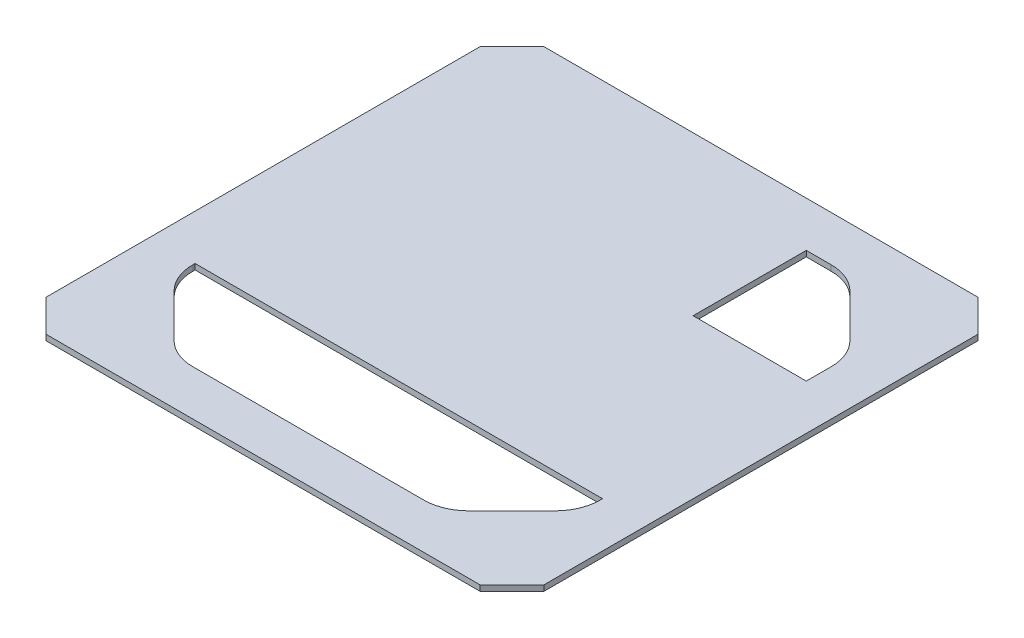
SolidWorks part; units mm, degrees
material "Thornel Mat VMA"
ref_plane "Front Plane" through (0, 0, 0) normal (0, 0, 1) x (1, 0, 0)
ref_plane "Top Plane" through (0, 0, 0) normal (0, 1, 0) x (1, 0, 0)
ref_plane "Right Plane" through (0, 0, 0) normal (1, 0, 0) x (0, 0, -1)
sketch "Sketch1" plane through (0, 0, 0) normal (0, 1, 0) x (1, 0, 0)
  line L0 (-139.7, 73.5201) -> (-121.7395, 91.4807)
  line L1 (-121.7395, 91.4807) -> (121.7395, 91.4807)
  line L2 (-139.7, 73.5201) -> (-139.7, -169.9588)
  line L3 (139.7, 73.5201) -> (139.7, -169.9588)
  line L4 (139.7, 73.5201) -> (121.7395, 91.4807)
  line L5 (0, 91.4807) -> (0, -187.9193) construction
  line L6 (-139.7, -48.2193) -> (139.7, -48.2193) construction
  line L7 (139.7, -169.9588) -> (121.7395, -187.9193)
  line L8 (-121.7395, -187.9193) -> (121.7395, -187.9193)
  line L9 (-139.7, -169.9588) -> (-121.7395, -187.9193)
  line L10 (-247.4631, 199.2437) -> (247.4631, 199.2437) construction
  line L11 (247.4631, 199.2437) -> (247.4631, -295.6824) construction
  line L12 (247.4631, -295.6824) -> (-247.4631, -295.6824) construction
  line L13 (-247.4631, -295.6824) -> (-247.4631, 199.2437) construction
  line L14 (-247.4631, 199.2437) -> (247.4631, -295.6824) construction
  line L15 (-247.4631, -295.6824) -> (247.4631, 199.2437) construction
  line L16 (-247.4631, 199.2437) -> (-130.7197, 82.5004) construction
  point P11 (0, -48.2193)
  point P20 (0, -48.2193)
  point P21 (-130.7197, 82.5004)
  dimension "D1" = 279.4
  dimension "D2" = 279.4
  dimension "D3" = 25.4
  dimension "D4" = 165.1
extrude "Boss-Extrude1" add sketch "Sketch1" along normal blind 3.175
sketch "Sketch2" plane through (0, 3.175, 0) normal (0, 1, 0) x (1, 0, 0)
  line L0 (-139.7, -48.2193) -> (139.7, -48.2193) construction
  line L1 (-139.7, 73.5201) -> (-139.7, -169.9588) construction
  line L2 (-103.779, 37.5991) -> (-114.3, 27.0781)
  line L3 (0, 91.4807) -> (0, -187.9193) construction
  line L4 (-85.8185, 55.5596) -> (-75.2974, 66.0807)
  line L5 (-130.7197, 82.5004) -> (-94.7987, 46.5794) construction
  line L6 (121.7395, 91.4807) -> (-121.7395, 91.4807) construction
  line L7 (-121.7395, -187.9193) -> (121.7395, -187.9193) construction
  line L8 (139.7, -169.9588) -> (139.7, 73.5201) construction
  line L9 (-114.3, 27.0781) -> (-114.3, -123.5168)
  line L10 (-121.7395, 91.4807) -> (-139.7, 73.5201) construction
  line L11 (-75.2974, 66.0807) -> (75.2974, 66.0807)
  line L12 (114.3, 27.0781) -> (114.3, -123.5168)
  line L13 (85.8185, 55.5596) -> (103.779, 37.5991)
  line L14 (85.8185, 55.5596) -> (75.2974, 66.0807)
  line L15 (103.779, 37.5991) -> (114.3, 27.0781)
  line L16 (-85.8185, -151.9983) -> (-103.779, -134.0378)
  line L17 (103.779, -134.0378) -> (114.3, -123.5168)
  line L18 (85.8185, -151.9983) -> (75.2974, -162.5193)
  line L19 (85.8185, -151.9983) -> (103.779, -134.0378)
  line L20 (-75.2974, -162.5193) -> (75.2974, -162.5193)
  line L21 (-85.8185, -151.9983) -> (-75.2974, -162.5193)
  line L22 (-103.779, -134.0378) -> (-114.3, -123.5168)
  line L23 (-85.8185, 55.5596) -> (-103.779, 37.5991)
  point P22 (114.3, -48.2193)
  point P26 (-114.3, -48.2193)
  dimension "D3" = 25.4
  dimension "D4" = 25.4
  dimension "D1" = 50.8
  dimension "D2" = 25.4
extrude "Cut-Extrude4" cut sketch "Sketch2" against normal through all
sketch "Sketch5" plane through (0, 3.175, 0) normal (0, 1, 0) x (1, 0, 0)
  line L0 (0, 91.4807) -> (0, -187.9193) construction
  line L1 (121.7395, 91.4807) -> (-121.7395, 91.4807) construction
  line L2 (139.7, -48.2193) -> (-139.7, -48.2193) construction
  line L3 (139.7, -169.9588) -> (139.7, 73.5201) construction
  line L4 (-121.7395, -187.9193) -> (121.7395, -187.9193) construction
  line L5 (-139.7, 73.5201) -> (-139.7, -169.9588) construction
  line L6 (-247.4631, 199.2437) -> (247.4631, 199.2437) construction
  line L7 (247.4631, 199.2437) -> (247.4631, -295.6824) construction
  line L8 (247.4631, -295.6824) -> (-247.4631, -295.6824) construction
  line L9 (-247.4631, -295.6824) -> (-247.4631, 199.2437) construction
  line L10 (139.7, -48.2193) -> (358.8347, -48.2193) construction
  line L11 (0, 91.4807) -> (0, 307.0068) construction
  line L12 (-247.4631, 199.2437) -> (247.4631, -295.6824) construction
  line L13 (247.4631, 199.2437) -> (-247.4631, -295.6824) construction
  line L14 (-121.7395, 91.4807) -> (-139.7, 73.5201) construction
  line L15 (-247.4631, 199.2437) -> (-94.7987, 46.5794) construction
  line L16 (-75.2974, 66.0807) -> (-114.3, 27.0781) construction
  circle A0 centre (-121.7395, 73.5201) radius 2.54
  circle A1 centre (-103.779, 55.5596) radius 2.54
  circle A2 centre (103.779, 55.5596) radius 2.54
  circle A3 centre (121.7395, 73.5201) radius 2.54
  circle A4 centre (121.7395, -169.9588) radius 2.54
  circle A5 centre (103.779, -151.9983) radius 2.54
  circle A6 centre (-103.779, -151.9983) radius 2.54
  circle A7 centre (-121.7395, -169.9588) radius 2.54
  point P9 (247.4631, -48.2193)
  point P19 (0, 199.2437)
  dimension "D2" = 5.08
  dimension "D3" = 5.08
  dimension "D1" = 165.1
  dimension "D4" = 25.4
  dimension "D5" = 12.7
extrude "Cut-Extrude3" [suppressed] cut sketch "Sketch5" against normal through all
sketch "Sketch4" plane through (0, 3.175, 0) normal (0, 1, 0) x (1, 0, 0)
  line L0 (-139.7, -48.2193) -> (171.6111, -48.2193) construction
  line L1 (-139.7, 73.5201) -> (-139.7, -169.9588) construction
  line L2 (121.7395, 91.4807) -> (-121.7395, 91.4807) construction
  line L3 (0, -48.2193) -> (0, -217.7016) construction
  line L4 (139.7, -169.9588) -> (139.7, 73.5201) construction
  line L5 (0, -48.2193) -> (0, 293.0757) construction
  circle A0 centre (0, 81.3207) radius 2.159
  circle A1 centre (-44.45, 81.3207) radius 2.159
  circle A2 centre (44.45, 81.3207) radius 2.159
  circle A3 centre (-22.225, 81.3207) radius 2.159
  circle A4 centre (22.225, 81.3207) radius 2.159
  circle A5 centre (-129.54, -48.2193) radius 2.159
  circle A6 centre (-129.54, -25.9943) radius 2.159
  circle A7 centre (-129.54, -3.7693) radius 2.159
  circle A8 centre (129.54, -48.2193) radius 2.159
  circle A9 centre (129.54, -25.9943) radius 2.159
  circle A10 centre (129.54, -3.7693) radius 2.159
  circle A11 centre (129.54, -92.6693) radius 2.159
  circle A12 centre (129.54, -70.4443) radius 2.159
  circle A13 centre (-129.54, -92.6693) radius 2.159
  circle A14 centre (-129.54, -70.4443) radius 2.159
  circle A15 centre (22.225, -177.7593) radius 2.159
  circle A16 centre (-22.225, -177.7593) radius 2.159
  circle A17 centre (44.45, -177.7593) radius 2.159
  circle A18 centre (-44.45, -177.7593) radius 2.159
  circle A19 centre (0, -177.7593) radius 2.159
  circle A20 centre (-66.675, 81.3207) radius 2.159
  circle A21 centre (66.675, 81.3207) radius 2.159
  circle A22 centre (-129.54, 18.4557) radius 2.159
  circle A23 centre (129.54, 18.4557) radius 2.159
  circle A24 centre (129.54, -114.8943) radius 2.159
  circle A25 centre (66.675, -177.7593) radius 2.159
  circle A26 centre (-66.675, -177.7593) radius 2.159
  circle A27 centre (-129.54, -114.8943) radius 2.159
  circle A28 centre (-129.54, -137.1193) radius 2.159
  circle A29 centre (-129.54, 40.6807) radius 2.159
  circle A30 centre (129.54, 40.6807) radius 2.159
  circle A31 centre (129.54, -137.1193) radius 2.159
  point P48 (0, 91.4807)
  dimension "D1" = 4.318
  dimension "D2" = 4.318
  dimension "D3" = 4.318
  dimension "D4" = 4.318
  dimension "D5" = 4.318
  dimension "D6" = 4.318
  dimension "D7" = 4.318
  dimension "D8" = 4.318
  dimension "D9" = 4.318
  dimension "D10" = 4.318
  dimension "D11" = 4.318
  dimension "D23" = 4.318
  dimension "D24" = 4.318
  dimension "D27" = 4.318
  dimension "D28" = 4.318
  dimension "D31" = 4.318
  dimension "D12" = 22.225
  dimension "D13" = 22.225
  dimension "D14" = 22.225
  dimension "D15" = 22.225
  dimension "D16" = 22.225
  dimension "D17" = 22.225
  dimension "D18" = 22.225
  dimension "D19" = 22.225
  dimension "D20" = 10.16
  dimension "D21" = 10.16
  dimension "D22" = 10.16
  dimension "D25" = 22.225
  dimension "D26" = 22.225
  dimension "D29" = 22.225
  dimension "D30" = 22.225
  dimension "D32" = 22.225
extrude "Cut-Extrude2" [suppressed] cut sketch "Sketch4" against normal through all
fillet "Fillet1" radius 25.4 8 edges at (114.3, 1.5875, 123.5168) (75.2974, 1.5875, 162.5193) (-75.2974, 1.5875, 162.5193) (-114.3, 1.5875, 123.5168) (114.3, 1.5875, -27.0781) (75.2974, 1.5875, -66.0807) (-114.3, 1.5875, -27.0781) (-75.2974, 1.5875, -66.0807)
sketch "Sketch6" plane through (0, 3.175, 0) normal (0, 1, 0) x (1, 0, 0)
  line L0 (-139.7, 73.5201) -> (-139.7, -169.9588) construction
  line L1 (50.8, 2.5807) -> (139.7, 2.5807)
  line L2 (-139.7, 2.5807) -> (-139.7, -111.7193)
  line L3 (-139.7, -111.7193) -> (139.7, -111.7193)
  line L4 (139.7, 2.5807) -> (139.7, -111.7193)
  line L5 (139.7, -169.9588) -> (139.7, 73.5201) construction
  line L6 (121.7395, 91.4807) -> (-121.7395, 91.4807) construction
  line L7 (-121.7395, -187.9193) -> (121.7395, -187.9193) construction
  line L10 (50.8, 2.5807) -> (50.8, 73.5201)
  line L11 (50.8, 73.5201) -> (-139.7, 73.5201)
  line L12 (-139.7, 2.5807) -> (-139.7, 73.5201)
  dimension "D1" = 88.9
  dimension "D2" = 76.2
  dimension "D3" = 88.9
extrude "Boss-Extrude2" add sketch "Sketch6" against normal up to surface (3.175 mm away) up to face at (0, 0, 48.2193)
